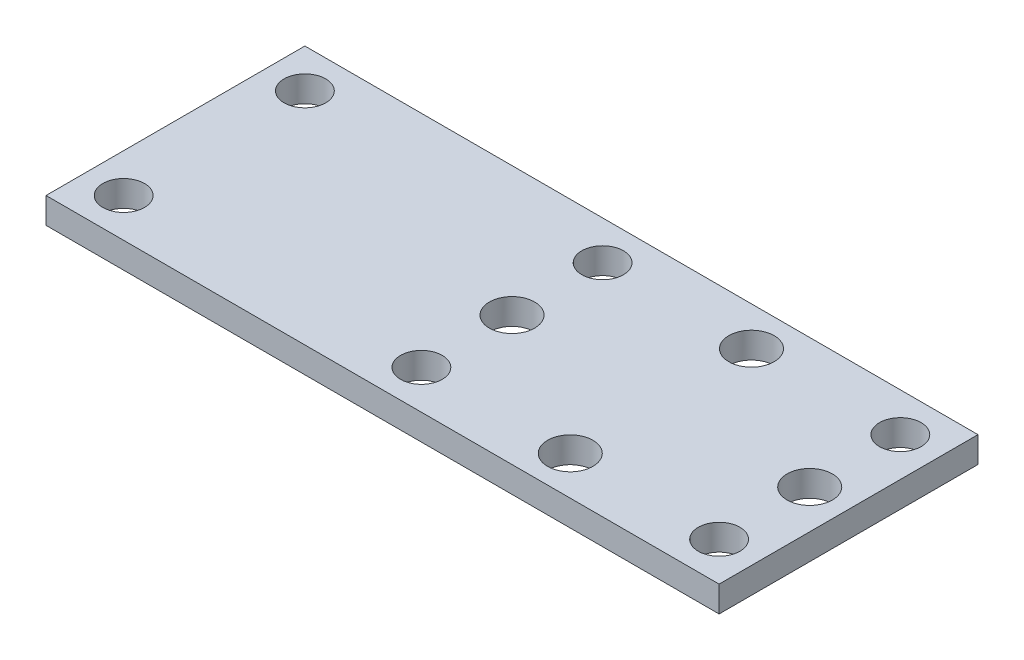
SolidWorks part; units mm, degrees
material "6061 Alloy"
ref_plane "Front Plane" through (0, 0, 0) normal (0, 0, 1) x (1, 0, 0)
ref_plane "Top Plane" through (0, 0, 0) normal (0, 1, 0) x (1, 0, 0)
ref_plane "Right Plane" through (0, 0, 0) normal (1, 0, 0) x (0, 0, -1)
sketch "Sketch1" plane through (0, 0, 0) normal (0, 1, 0) x (1, 0, 0)
  line L1 (-41.275, -15.875) -> (41.275, -15.875)
  line L2 (-41.275, -15.875) -> (-41.275, 15.875)
  line L3 (-41.275, 15.875) -> (41.275, 15.875)
  line L4 (41.275, -15.875) -> (41.275, 15.875)
  line L5 (-41.275, -15.875) -> (41.275, 15.875) construction
  line L6 (-41.275, 15.875) -> (41.275, -15.875) construction
  point P0 (0, 0)
  dimension "D1" = 82.55
  dimension "D2" = 31.75
extrude "Plate" add sketch "Sketch1" along normal mid plane 3.175
hole_wizard "#10 Clearance Hole1" positions "Sketch3" profile "Sketch2" hole size "#10" standard "ANSI Inch" end condition through all
sketch "Sketch3" plane through (0, 1.5875, 0) normal (0, 1, 0) x (1, 0, 0)
  line L12 (36.5125, -11.1125) -> (36.5125, 11.1125)
  line L13 (36.5125, 11.1125) -> (-36.5125, 11.1125)
  line L14 (-36.5125, 11.1125) -> (-36.5125, -11.1125)
  line L15 (-36.5125, -11.1125) -> (36.5125, -11.1125)
  line L16 (36.5125, -11.1125) -> (36.5125, 11.1125)
  line L17 (36.5125, 11.1125) -> (-36.5125, 11.1125)
  line L18 (-36.5125, 11.1125) -> (-36.5125, -11.1125)
  line L19 (-36.5125, -11.1125) -> (36.5125, -11.1125)
  point P0 (-36.5125, 11.1125)
  point P4 (36.5125, 11.1125)
  point P6 (36.5125, -11.1125)
  point P10 (-36.5125, -11.1125)
  point P41 (0, -11.1125)
  point P43 (0, 11.1125)
  dimension "D1" = 4.7625
sketch "Sketch2" plane through (-36.5125, 1.5875, -11.1125) normal (1, 0, 0) x (0, 0, 1)
  line L0 (0, 0) -> (0, 3.175)
  line L1 (0, 3.175) -> (2.5527, 3.175)
  line L2 (2.5527, 3.175) -> (2.5527, 0)
  line L5 (2.5527, 0) -> (0, 0)
  line L11 (0, -6.35) -> (0, 107.95) construction
  dimension "Thru Hole Dia." = 5.1054
  dimension "Thru Hole Depth" = 3.175
hole_wizard "CBORE for #4 Socket Head Cap Screw1" positions "Sketch6" profile "Sketch5" counterbore size "#4" standard "ANSI Inch" end condition through all
sketch "Sketch6" plane through (0, 1.5875, 0) normal (0, 1, 0) x (1, 0, 0)
  line L1 (0, -11.1125) -> (36.5125, -11.1125)
  line L2 (0, -11.1125) -> (0, 11.1125)
  line L3 (0, 11.1125) -> (36.5125, 11.1125)
  line L4 (36.5125, -11.1125) -> (36.5125, 11.1125)
  line L5 (0, -11.1125) -> (36.5125, 11.1125) construction
  line L6 (0, 11.1125) -> (36.5125, -11.1125) construction
  point P0 (0, 0)
  point P3 (36.5125, 0)
  point P5 (18.2562, 11.1125)
  point P7 (18.2563, -11.1125)
sketch "Sketch5" plane through (0, 1.5875, 0) normal (1, 0, 0) x (0, 0, 1)
  line L0 (0, 0) -> (0, 3.175)
  line L1 (0, 3.175) -> (1.6319, 3.175)
  line L3 (1.6319, 3.175) -> (1.6319, 9.1948)
  line L4 (1.6319, 9.1948) -> (2.7788, 9.1948)
  line L5 (2.7788, 9.1948) -> (2.7788, 0)
  line L7 (2.7788, 0) -> (0, 0)
  line L11 (0, -6.35) -> (0, 107.95) construction
  dimension "Thru Hole Dia." = 3.2639
  dimension "Thru Hole Depth" = 3.175
  dimension "C'Bore Dia." = 5.5575
  dimension "C'Bore Depth" = 9.1948
